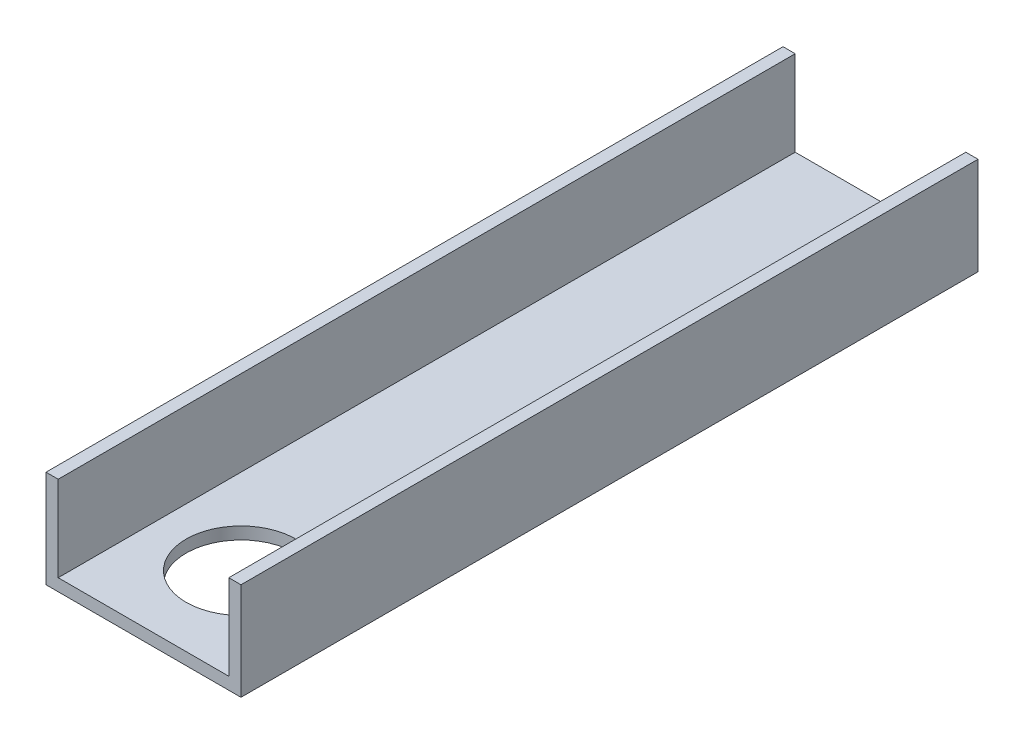
SolidWorks part; units mm, degrees
ref_plane "Front Plane" through (0, 0, 0) normal (0, 0, 1) x (1, 0, 0)
ref_plane "Top Plane" through (0, 0, 0) normal (0, 1, 0) x (1, 0, 0)
ref_plane "Right Plane" through (0, 0, 0) normal (1, 0, 0) x (0, 0, -1)
sketch "Sketch1" plane through (0, 0, 0) normal (0, 0, 1) x (1, 0, 0)
  line L0 (3.175, 3.175) -> (3.175, 25.4)
  line L1 (0, 0) -> (50.8, 0)
  line L2 (0, 0) -> (0, 25.4)
  line L3 (3.175, 3.175) -> (47.625, 3.175)
  line L4 (50.8, 0) -> (50.8, 25.4)
  line L5 (47.625, 3.175) -> (47.625, 25.4)
  line L6 (0, 25.4) -> (3.175, 25.4)
  line L7 (47.625, 25.4) -> (50.8, 25.4)
  dimension "D1" = 25.4
  dimension "D2" = 50.8
  dimension "D3" = 3.175
extrude "f" add sketch "Sketch1" along normal blind 192.024
sketch "Sketch2" plane through (0, 3.175, 0) normal (0, 1, 0) x (1, 0, 0)
  line L0 (25.4, -192.024) -> (25.4, -166.624) construction
  line L1 (47.625, -192.024) -> (3.175, -192.024) construction
  circle A0 centre (25.4, -166.624) radius 14.2875
  dimension "D2" = 28.575
  dimension "D1" = 25.4
extrude "Cut-Extrude1" cut sketch "Sketch2" against normal up to next
